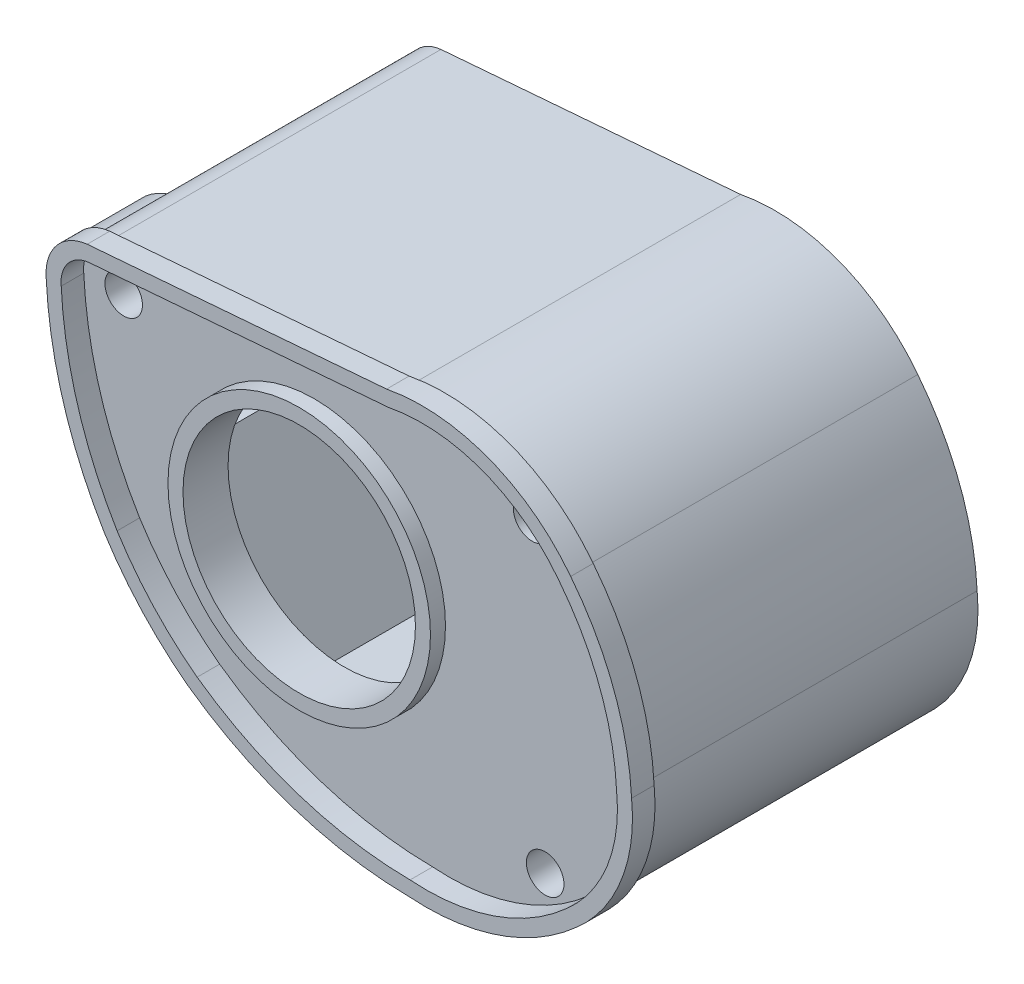
SolidWorks part; units mm, degrees
ref_plane "Front Plane" through (0, 0, 0) normal (0, 0, 1) x (1, 0, 0)
ref_plane "Top Plane" through (0, 0, 0) normal (0, 1, 0) x (1, 0, 0)
ref_plane "Right Plane" through (0, 0, 0) normal (1, 0, 0) x (0, 0, -1)
sketch "Sketch1" plane through (0, 0, 0) normal (0, 0, 1) x (1, 0, 0)
  line L0 (-33.46, 24.1054) -> (6.4406, 27.3373)
  circle A0 centre (-6.3282, 1.9316) radius 15.4733
  arc A1 (-38.0105, 18.4623) -> (-33.46, 24.1054) centre (-32.9137, 19.0086) cw
  arc A2 (-30.4253, -6.485) -> (-38.0105, 18.4623) centre (15.4722, 21.0968) cw
  arc A3 (-19.509, -18.305) -> (-30.4253, -6.485) centre (7.3126, 17.4168) cw
  arc A4 (9.3902, -27.6965) -> (-19.509, -18.305) centre (9.8018, 22.7299) cw
  arc A5 (30.9183, -20.3318) -> (9.3902, -27.6965) centre (11.5549, 1.1231) cw
  arc A6 (37.9235, -2.6186) -> (30.9183, -20.3318) centre (17.5379, -4.7984) cw
  arc A7 (30.0234, 18.3671) -> (37.9235, -2.6186) centre (1.2692, -4.4372) cw
  arc A8 (6.4406, 27.3373) -> (30.0234, 18.3671) centre (11.0089, 3.8623) cw
extrude "Boss-Extrude1" add sketch "Sketch1" along normal blind 44
sketch "Sketch2" plane through (0, 0, 0) normal (0, 0, -1) x (-1, 0, 0)
  line L8 (32.5892, 16.133) -> (-19.3957, 20.842)
  line L9 (-19.3957, 20.842) -> (-20.5547, 18.9298)
  line L10 (-20.5547, 18.9298) -> (-21.6028, 10.9886)
  line L11 (2.6863, -19.0823) -> (14.1484, -20.0158)
  line L12 (14.1484, -20.0158) -> (25.9824, 2.0966)
  line L13 (25.9824, 2.0966) -> (30.0476, 1.7655)
  line L14 (32.5892, 16.133) -> (31.6395, 4.3573)
  arc A3 (-21.6028, 10.9886) -> (-26.5345, -12.0015) centre (83.2924, -23.5371) ccw
  arc A4 (-26.5345, -12.0015) -> (2.6863, -19.0823) centre (-9.6252, -6.0549) ccw
  arc A5 (30.0476, 1.7655) -> (31.6395, 4.3573) centre (40.3745, -2.7928) cw
extrude "Cut-Extrude1" cut sketch "Sketch2" against normal blind 40
sketch "Sketch11" plane through (0, 0, 44) normal (0, 0, 1) x (1, 0, 0)
  circle A0 centre (22.6828, 19.9781) radius 2.5
  circle A1 centre (-31.6938, 18.7566) radius 2.5
  circle A2 centre (24.4191, -19.9532) radius 2.5
extrude "Cut-Extrude5" cut sketch "Sketch11" against normal blind 5
sketch "Sketch13" plane through (0, 0, 44) normal (0, 0, 1) x (1, 0, 0)
  circle A0 centre (-31.7576, 18.7335) radius 1.5
  circle A1 centre (22.712, 19.9715) radius 1.5
  circle A2 centre (24.3374, -19.9971) radius 1.5
extrude "Cut-Extrude6" cut sketch "Sketch13" against normal blind 10
sketch "Sketch14" plane through (0, 0, 44) normal (0, 0, 1) x (1, 0, 0)
  line L2 (6.5775, 26.3451) -> (-33.3656, 23.1097)
  line L3 (6.5775, 26.3451) -> (-33.3656, 23.1097)
  arc A16 (-37.0132, 18.5417) -> (-29.5743, -5.9598) centre (15.4722, 21.0968) ccw
  arc A17 (-29.5743, -5.9598) -> (-18.9181, -17.4982) centre (7.3126, 17.4168) ccw
  arc A18 (-18.9181, -17.4982) -> (9.4319, -26.6968) centre (9.8018, 22.7299) ccw
  arc A19 (9.4319, -26.6968) -> (30.257, -19.5816) centre (11.5549, 1.1231) ccw
  arc A20 (30.257, -19.5816) -> (36.9261, -2.6968) centre (17.5379, -4.7984) ccw
  arc A21 (36.9261, -2.6968) -> (29.2341, 17.7532) centre (1.2692, -4.4372) ccw
  arc A22 (29.2341, 17.7532) -> (6.5775, 26.3451) centre (11.0089, 3.8623) ccw
  arc A23 (-33.3656, 23.1097) -> (-37.0132, 18.5417) centre (-32.9137, 19.0086) ccw
  arc A24 (-37.0132, 18.5417) -> (-29.5743, -5.9598) centre (15.4722, 21.0968) ccw
  arc A25 (-29.5743, -5.9598) -> (-18.9181, -17.4982) centre (7.3126, 17.4168) ccw
  arc A26 (-18.9181, -17.4982) -> (9.4319, -26.6968) centre (9.8018, 22.7299) ccw
  arc A27 (9.4319, -26.6968) -> (30.257, -19.5816) centre (11.5549, 1.1231) ccw
  arc A28 (30.257, -19.5816) -> (36.9261, -2.6968) centre (17.5379, -4.7984) ccw
  arc A29 (36.9261, -2.6968) -> (29.2341, 17.7532) centre (1.2692, -4.4372) ccw
  arc A30 (29.2341, 17.7532) -> (6.5775, 26.3451) centre (11.0089, 3.8623) ccw
  arc A31 (-33.3656, 23.1097) -> (-37.0132, 18.5417) centre (-32.9137, 19.0086) ccw
  dimension "D1" = 1
extrude "Extrude-Thin1" add sketch "Sketch14" along normal blind 3 thin
sketch "Sketch15" plane through (0, 0, 44) normal (0, 0, 1) x (1, 0, 0)
  circle A2 centre (-6.3282, 1.9316) radius 15.4733
  circle A3 centre (-6.3282, 1.9316) radius 15.4733
  dimension "D1" = 0
extrude "Extrude-Thin2" add sketch "Sketch15" along normal blind 2 thin
ref_plane "Plane1" through (0, 0, 20) normal (0, 0, 1) x (1, 0, 0)
sketch "Sketch16" plane through (0, 0, 20) normal (0, 0, 1) x (1, 0, 0)
  line L0 (-46.8622, 9.7634) -> (-36.8622, 9.7634)
  line L1 (-46.8622, -8.235) -> (-29.2583, -8.235)
  arc A2 (-36.8622, 9.7634) -> (-29.2583, -8.235) centre (13.9627, 20.6303) ccw
  circle A3 centre (-46.8622, 0.7642) radius 8.9992
  arc A5 (-38.0105, 18.4623) -> (-30.4253, -6.485) centre (15.4722, 21.0968) ccw construction
  circle A6 centre (-46.8622, 0.7642) radius 4.5
  arc A7 (-30.4253, -6.485) -> (-19.509, -18.305) centre (7.3126, 17.4168) ccw construction
extrude "Boss-Extrude3" add sketch "Sketch16" along normal blind 10 separate body
